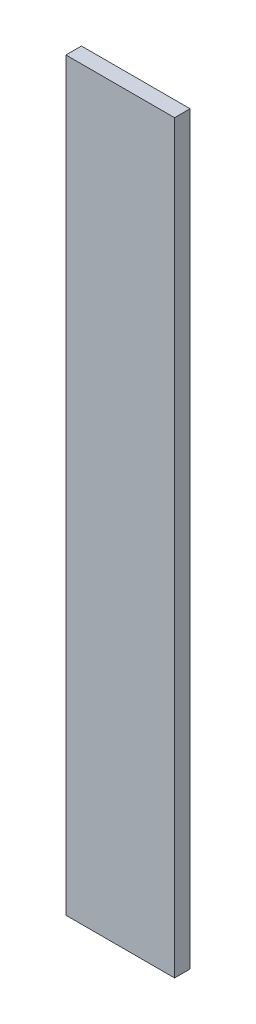
SolidWorks part; units mm, degrees
ref_plane "Front Plane" through (0, 0, 0) normal (0, 0, 1) x (1, 0, 0)
ref_plane "Top Plane" through (0, 0, 0) normal (0, 1, 0) x (1, 0, 0)
ref_plane "Right Plane" through (0, 0, 0) normal (1, 0, 0) x (0, 0, -1)
sketch "Sketch1" plane through (0, 0, 0) normal (0, 1, 0) x (1, 0, 0)
  line L1 (0, 0) -> (44.45, 0)
  line L2 (0, 0) -> (0, 6.35)
  line L3 (0, 6.35) -> (44.45, 6.35)
  line L4 (44.45, 0) -> (44.45, 6.35)
  dimension "D1" = 6.35
  dimension "D2" = 44.45
extrude "Boss-Extrude1" add sketch "Sketch1" along normal blind 304.8
